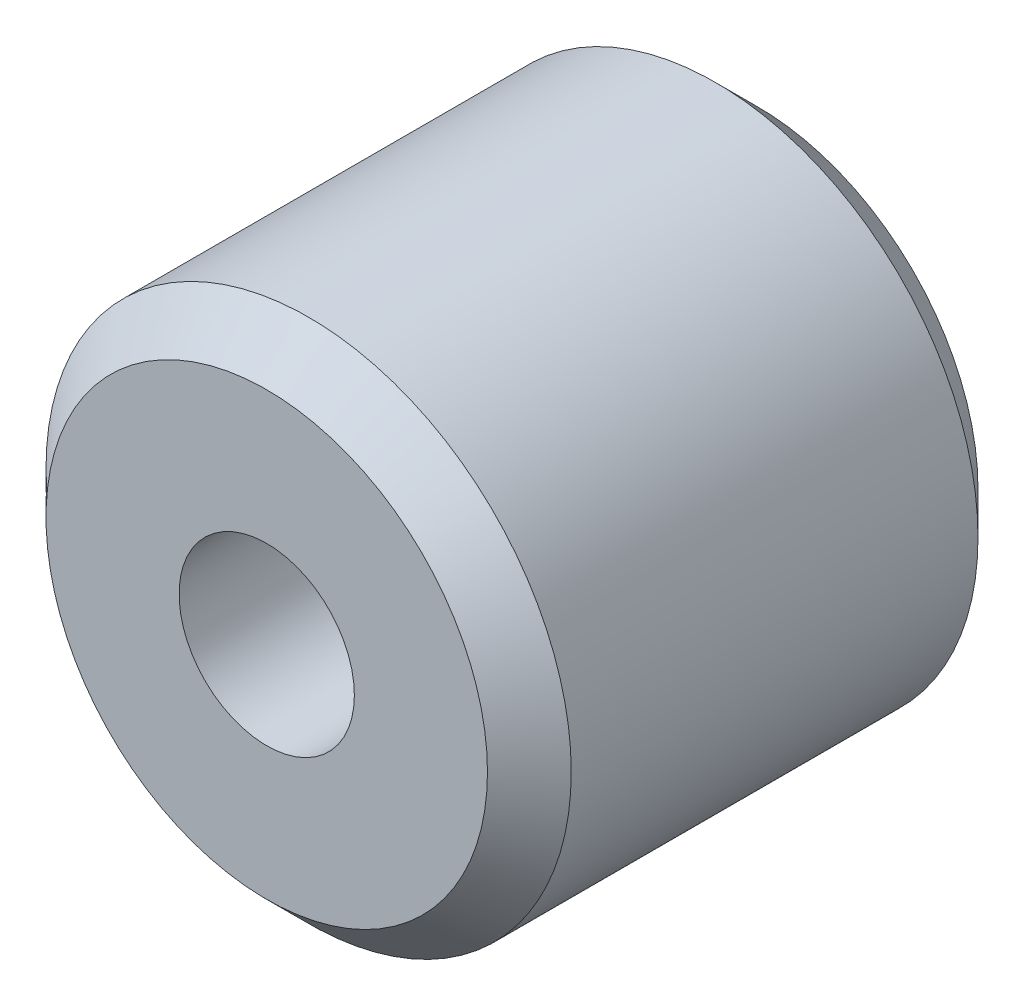
SolidWorks part; units mm, degrees
ref_plane "Front Plane" through (0, 0, 0) normal (0, 0, 1) x (1, 0, 0)
ref_plane "Top Plane" through (0, 0, 0) normal (0, 1, 0) x (1, 0, 0)
ref_plane "Right Plane" through (0, 0, 0) normal (1, 0, 0) x (0, 0, -1)
sketch "Sketch1" plane through (0, 0, 0) normal (0, 0, 1) x (1, 0, 0)
  circle A0 centre (0, 0) radius 1.59
  circle A1 centre (0, 0) radius 4.765
  dimension "D1" = 3.18
  dimension "D2" = 9.53
extrude "Boss-Extrude1" add sketch "Sketch1" along normal mid plane 8.9
chamfer "Chamfer1" distance 0.76 angle 45 2 edges at (4.765, 0, -4.45) (4.765, 0, 4.45)
